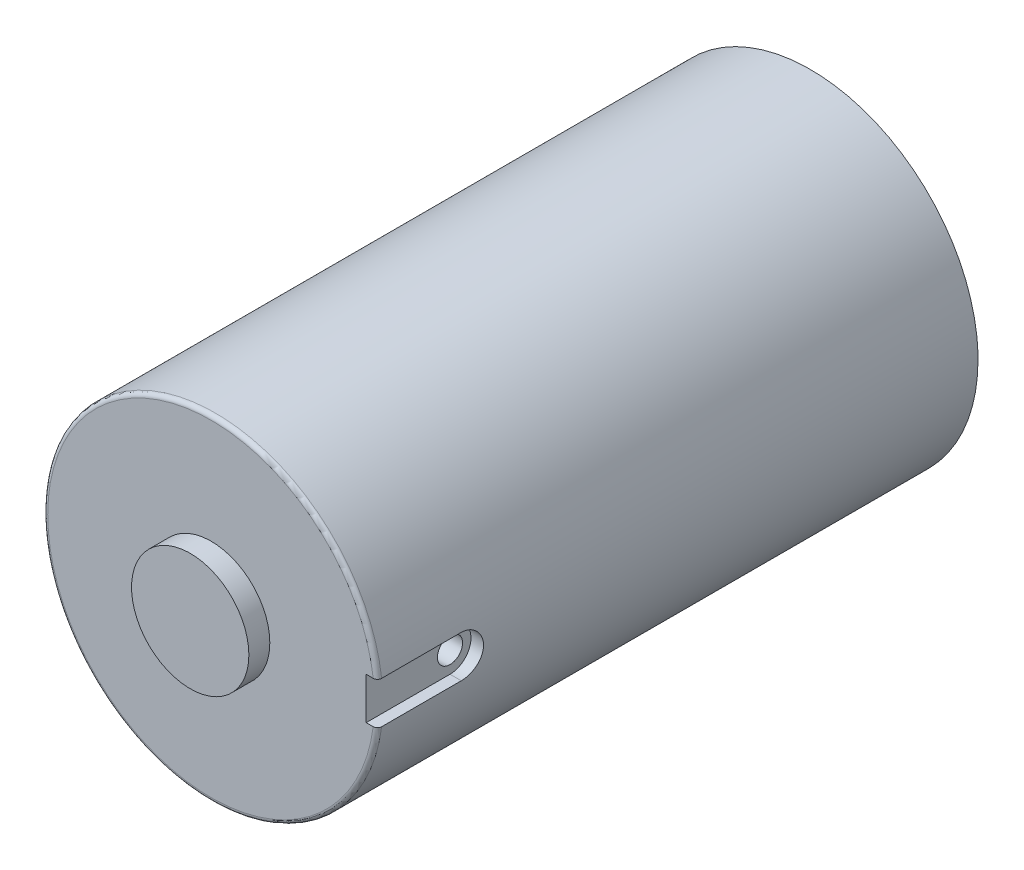
SolidWorks part; units mm, degrees
ref_plane "前视基准面" through (0, 0, 0) normal (0, 0, 1) x (1, 0, 0)
ref_plane "上视基准面" through (0, 0, 0) normal (0, 1, 0) x (1, 0, 0)
ref_plane "右视基准面" through (0, 0, 0) normal (1, 0, 0) x (0, 0, -1)
sketch "草图1" plane through (0, 0, 0) normal (0, 0, 1) x (1, 0, 0)
  circle A0 centre (0, 0) radius 40
  dimension "D1" = 80
extrude "凸台-拉伸1" add sketch "草图1" along normal blind 113
sketch "草图2" plane through (0, 0, 113) normal (0, 0, 1) x (1, 0, 0)
  circle A0 centre (0, 0) radius 40 construction
  circle A1 centre (0, 0) radius 40
extrude "凸台-拉伸2" add sketch "草图2" along normal blind 30
sketch "草图3" plane through (0, 0, 143) normal (0, 0, 1) x (1, 0, 0)
  circle A0 centre (0, 0) radius 14
  dimension "D1" = 28
extrude "凸台-拉伸3" add sketch "草图3" along normal blind 5
sketch "草图4" plane through (0, 0, 0) normal (1, 0, 0) x (0, 0, -1)
  line L1 (-143, 14) -> (-143, -14) construction
  line L2 (-143, 0) -> (-143, 5)
  line L3 (-143, 0) -> (-143, -5)
  line L4 (-143, 5) -> (-123, 5)
  line L5 (-143, -5) -> (-123, -5)
  arc A0 (-123, -5) -> (-123, 5) centre (-123, 0) ccw
  dimension "D1" = 20
  dimension "D2" = 5
  dimension "D3" = 5
ref_plane "基准面4" through (37, 0, 0) normal (1, 0, 0) x (0, 0, -1)
sketch "草图5" plane through (37, 0, 0) normal (1, 0, 0) x (0, 0, -1)
  line L0 (-143, 0) -> (-143, -5) construction
  line L1 (-143, 0) -> (-143, 5) construction
  line L2 (-143, -5) -> (-123, -5) construction
  line L3 (-143, 5) -> (-123, 5) construction
  line L4 (-143, 0) -> (-143, -5)
  line L5 (-143, 0) -> (-143, 5)
  line L6 (-143, -5) -> (-123, -5)
  line L7 (-143, 5) -> (-123, 5)
  arc A0 (-123, -5) -> (-123, 5) centre (-123, 0) ccw construction
  arc A1 (-123, -5) -> (-123, 5) centre (-123, 0) ccw
extrude "切除-拉伸1" cut sketch "草图5" along normal blind 34
sketch "草图6" plane through (37, 0, 0) normal (1, 0, 0) x (0, 0, -1)
  circle A0 centre (-123, 0) radius 3
  dimension "D1" = 6
extrude "切除-拉伸2" cut sketch "草图6" against normal blind 10
fillet "圆角1" radius 1 1 edges at (-40, 0, 143)
